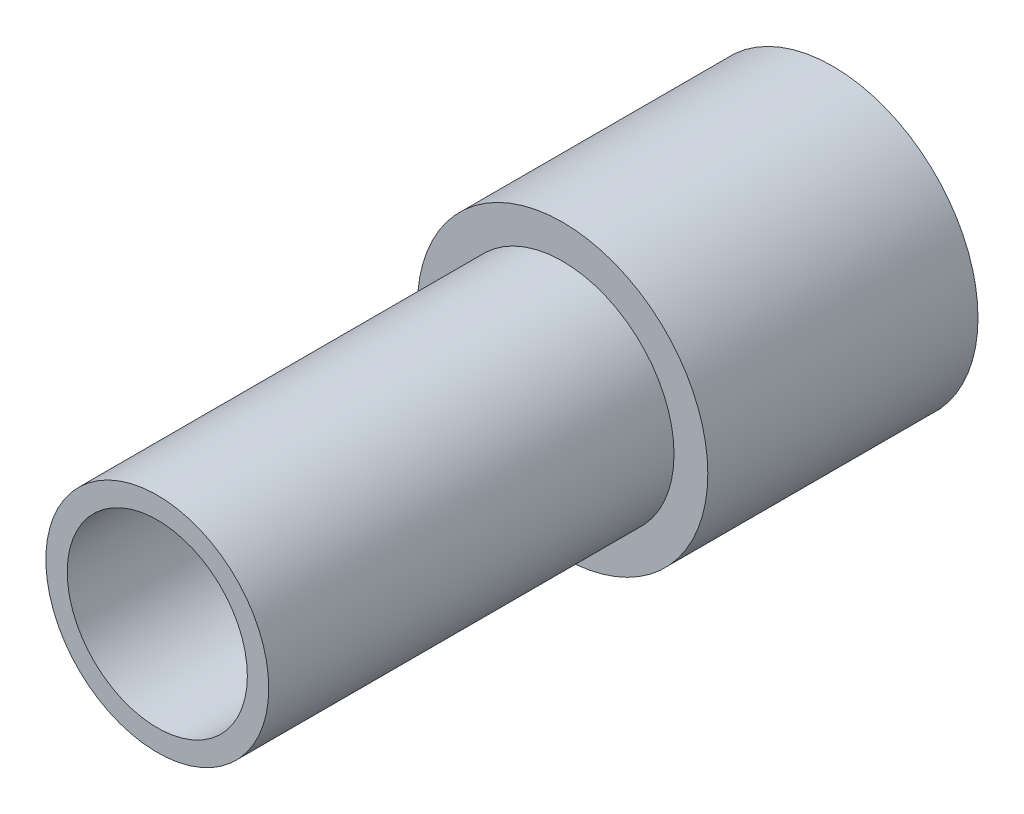
SolidWorks part; units mm, degrees
ref_plane "Front Plane" through (0, 0, 0) normal (0, 0, 1) x (1, 0, 0)
ref_plane "Top Plane" through (0, 0, 0) normal (0, 1, 0) x (1, 0, 0)
ref_plane "Right Plane" through (0, 0, 0) normal (1, 0, 0) x (0, 0, -1)
sketch "Sketch1" plane through (0, 0, 0) normal (0, 0, 1) x (1, 0, 0)
  circle A0 centre (0, 0) radius 6.45
  circle A1 centre (0, 0) radius 4
  dimension "D1" = 12.9
  dimension "D2" = 8
extrude "Boss-Extrude1" add sketch "Sketch1" along normal blind 30
sketch "Sketch2" plane through (0, 0, 30) normal (0, 0, 1) x (1, 0, 0)
  circle A0 centre (0, 0) radius 4.95
  circle A1 centre (0, 0) radius 6.45
  circle A2 centre (0, 0) radius 6.45 construction
  dimension "D1" = 9.9
extrude "Cut-Extrude1" cut sketch "Sketch2" against normal blind 18
